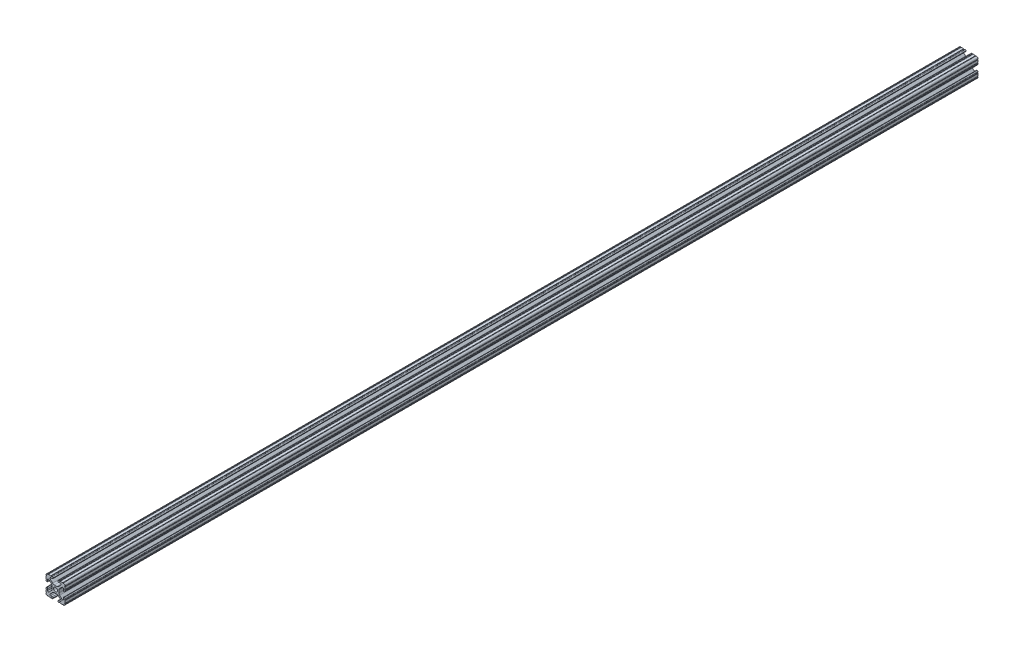
SolidWorks part; units mm, degrees
ref_plane "Front Plane" through (0, 0, 0) normal (0, 0, 1) x (1, 0, 0)
ref_plane "Top Plane" through (0, 0, 0) normal (0, 1, 0) x (1, 0, 0)
ref_plane "Right Plane" through (0, 0, 0) normal (1, 0, 0) x (0, 0, -1)
sketch "Sketch1" plane through (0, 0, 0) normal (0, 0, 1) x (1, 0, 0)
  line L88 (-7.1797, -8.6452) -> (-3.9523, -5.4237)
  line L89 (-1.7093, -4.4958) -> (1.7093, -4.4958)
  line L90 (3.9523, -5.4237) -> (7.1797, -8.6452)
  line L91 (6.4164, -10.4902) -> (4.2875, -10.4902)
  line L92 (3.2385, -11.5392) -> (3.2385, -11.651)
  line L93 (4.2875, -12.7) -> (5.3171, -12.7)
  line L94 (6.3331, -12.7) -> (9.5504, -12.7)
  line L95 (12.7, -9.5504) -> (12.7, -6.3331)
  line L96 (12.7, -5.3171) -> (12.7, -4.2875)
  line L97 (11.651, -3.2385) -> (11.5392, -3.2385)
  line L98 (10.4902, -4.2875) -> (10.4902, -6.4021)
  line L99 (8.7371, -7.1294) -> (5.441, -3.8408)
  line L100 (4.5085, -1.5932) -> (4.5085, 1.5932)
  line L101 (5.441, 3.8408) -> (8.7371, 7.1294)
  line L102 (10.4902, 6.4021) -> (10.4902, 4.2875)
  line L103 (11.5392, 3.2385) -> (11.651, 3.2385)
  line L104 (12.7, 4.2875) -> (12.7, 5.3171)
  line L105 (12.7, 6.3331) -> (12.7, 9.5504)
  line L106 (9.5504, 12.7) -> (6.3331, 12.7)
  line L107 (5.3171, 12.7) -> (4.2875, 12.7)
  line L108 (3.2385, 11.651) -> (3.2385, 11.5392)
  line L109 (4.2875, 10.4902) -> (6.4768, 10.4902)
  line L110 (7.207, 8.7244) -> (3.8983, 5.4232)
  line L111 (1.6558, 4.4958) -> (-1.6558, 4.4958)
  line L112 (-3.8983, 5.4232) -> (-7.207, 8.7244)
  line L113 (-6.4768, 10.4902) -> (-4.2875, 10.4902)
  line L114 (-3.2385, 11.5392) -> (-3.2385, 11.651)
  line L115 (-4.2875, 12.7) -> (-5.3171, 12.7)
  line L116 (-6.3331, 12.7) -> (-9.5504, 12.7)
  line L117 (-12.7, 9.5504) -> (-12.7, 6.3331)
  line L118 (-12.7, 5.3171) -> (-12.7, 4.2875)
  line L119 (-11.651, 3.2385) -> (-11.5392, 3.2385)
  line L120 (-10.4902, 4.2875) -> (-10.4902, 6.4021)
  line L121 (-8.7371, 7.1294) -> (-5.441, 3.8408)
  line L122 (-4.5085, 1.5932) -> (-4.5085, -1.5932)
  line L123 (-5.441, -3.8408) -> (-8.7371, -7.1294)
  line L124 (-10.4902, -6.4021) -> (-10.4902, -4.2875)
  line L125 (-11.5392, -3.2385) -> (-11.651, -3.2385)
  line L126 (-12.7, -4.2875) -> (-12.7, -5.3171)
  line L127 (-12.7, -6.3331) -> (-12.7, -9.5504)
  line L128 (-9.5504, -12.7) -> (-6.3331, -12.7)
  line L129 (-5.3171, -12.7) -> (-4.2875, -12.7)
  line L130 (-3.2385, -11.651) -> (-3.2385, -11.5392)
  line L131 (-4.2875, -10.4902) -> (-6.4164, -10.4902)
  circle A1 centre (0, 0) radius 2.6035
  arc A104 (-7.1797, -8.6452) -> (-6.4164, -10.4902) centre (-6.4164, -9.4098) ccw
  arc A105 (-1.7093, -4.4958) -> (-3.9523, -5.4237) centre (-1.7093, -7.6708) ccw
  arc A106 (3.9523, -5.4237) -> (1.7093, -4.4958) centre (1.7093, -7.6708) ccw
  arc A107 (6.4164, -10.4902) -> (7.1797, -8.6452) centre (6.4164, -9.4098) ccw
  arc A108 (4.2875, -10.4902) -> (3.2385, -11.5392) centre (4.2875, -11.5392) ccw
  arc A109 (3.2385, -11.651) -> (4.2875, -12.7) centre (4.2875, -11.651) ccw
  arc A110 (6.3331, -12.7) -> (5.3171, -12.7) centre (5.8251, -12.7) ccw
  arc A111 (10.5664, -12.6998) -> (9.5504, -12.7) centre (10.0584, -12.7) ccw
  arc A112 (10.5664, -12.6998) -> (12.6998, -10.5664) centre (10.5918, -10.5918) ccw
  arc A113 (12.7, -9.5504) -> (12.6998, -10.5664) centre (12.7, -10.0584) ccw
  arc A114 (12.7, -5.3171) -> (12.7, -6.3331) centre (12.7, -5.8251) ccw
  arc A115 (12.7, -4.2875) -> (11.651, -3.2385) centre (11.651, -4.2875) ccw
  arc A116 (11.5392, -3.2385) -> (10.4902, -4.2875) centre (11.5392, -4.2875) ccw
  arc A117 (8.7371, -7.1294) -> (10.4902, -6.4021) centre (9.4628, -6.4021) ccw
  arc A118 (4.5085, -1.5932) -> (5.441, -3.8408) centre (7.6835, -1.5932) ccw
  arc A119 (5.441, 3.8408) -> (4.5085, 1.5932) centre (7.6835, 1.5932) ccw
  arc A120 (10.4902, 6.4021) -> (8.7371, 7.1294) centre (9.4628, 6.4021) ccw
  arc A121 (10.4902, 4.2875) -> (11.5392, 3.2385) centre (11.5392, 4.2875) ccw
  arc A122 (11.651, 3.2385) -> (12.7, 4.2875) centre (11.651, 4.2875) ccw
  arc A123 (12.7, 6.3331) -> (12.7, 5.3171) centre (12.7, 5.8251) ccw
  arc A124 (12.6998, 10.5664) -> (12.7, 9.5504) centre (12.7, 10.0584) ccw
  arc A125 (12.6998, 10.5664) -> (10.5664, 12.6998) centre (10.5918, 10.5918) ccw
  arc A126 (9.5504, 12.7) -> (10.5664, 12.6998) centre (10.0584, 12.7) ccw
  arc A127 (5.3171, 12.7) -> (6.3331, 12.7) centre (5.8251, 12.7) ccw
  arc A128 (4.2875, 12.7) -> (3.2385, 11.651) centre (4.2875, 11.651) ccw
  arc A129 (3.2385, 11.5392) -> (4.2875, 10.4902) centre (4.2875, 11.5392) ccw
  arc A130 (7.207, 8.7244) -> (6.4768, 10.4902) centre (6.4768, 9.4563) ccw
  arc A131 (1.6558, 4.4958) -> (3.8983, 5.4232) centre (1.6558, 7.6708) ccw
  arc A132 (-3.8983, 5.4232) -> (-1.6558, 4.4958) centre (-1.6558, 7.6708) ccw
  arc A133 (-6.4768, 10.4902) -> (-7.207, 8.7244) centre (-6.4768, 9.4563) ccw
  arc A134 (-4.2875, 10.4902) -> (-3.2385, 11.5392) centre (-4.2875, 11.5392) ccw
  arc A135 (-3.2385, 11.651) -> (-4.2875, 12.7) centre (-4.2875, 11.651) ccw
  arc A136 (-6.3331, 12.7) -> (-5.3171, 12.7) centre (-5.8251, 12.7) ccw
  arc A137 (-10.5664, 12.6998) -> (-9.5504, 12.7) centre (-10.0584, 12.7) ccw
  arc A138 (-10.5664, 12.6998) -> (-12.6998, 10.5664) centre (-10.5918, 10.5918) ccw
  arc A139 (-12.7, 9.5504) -> (-12.6998, 10.5664) centre (-12.7, 10.0584) ccw
  arc A140 (-12.7, 5.3171) -> (-12.7, 6.3331) centre (-12.7, 5.8251) ccw
  arc A141 (-12.7, 4.2875) -> (-11.651, 3.2385) centre (-11.651, 4.2875) ccw
  arc A142 (-11.5392, 3.2385) -> (-10.4902, 4.2875) centre (-11.5392, 4.2875) ccw
  arc A143 (-8.7371, 7.1294) -> (-10.4902, 6.4021) centre (-9.4628, 6.4021) ccw
  arc A144 (-4.5085, 1.5932) -> (-5.441, 3.8408) centre (-7.6835, 1.5932) ccw
  arc A145 (-5.441, -3.8408) -> (-4.5085, -1.5932) centre (-7.6835, -1.5932) ccw
  arc A146 (-10.4902, -6.4021) -> (-8.7371, -7.1294) centre (-9.4628, -6.4021) ccw
  arc A147 (-10.4902, -4.2875) -> (-11.5392, -3.2385) centre (-11.5392, -4.2875) ccw
  arc A148 (-11.651, -3.2385) -> (-12.7, -4.2875) centre (-11.651, -4.2875) ccw
  arc A149 (-12.7, -6.3331) -> (-12.7, -5.3171) centre (-12.7, -5.8251) ccw
  arc A150 (-12.6998, -10.5664) -> (-12.7, -9.5504) centre (-12.7, -10.0584) ccw
  arc A151 (-12.6998, -10.5664) -> (-10.5664, -12.6998) centre (-10.5918, -10.5918) ccw
  arc A152 (-9.5504, -12.7) -> (-10.5664, -12.6998) centre (-10.0584, -12.7) ccw
  arc A153 (-5.3171, -12.7) -> (-6.3331, -12.7) centre (-5.8251, -12.7) ccw
  arc A154 (-4.2875, -12.7) -> (-3.2385, -11.651) centre (-4.2875, -11.651) ccw
  arc A155 (-3.2385, -11.5392) -> (-4.2875, -10.4902) centre (-4.2875, -11.5392) ccw
extrude "Boss-Extrude1" add sketch "Sketch1" along normal mid plane 1219.2
